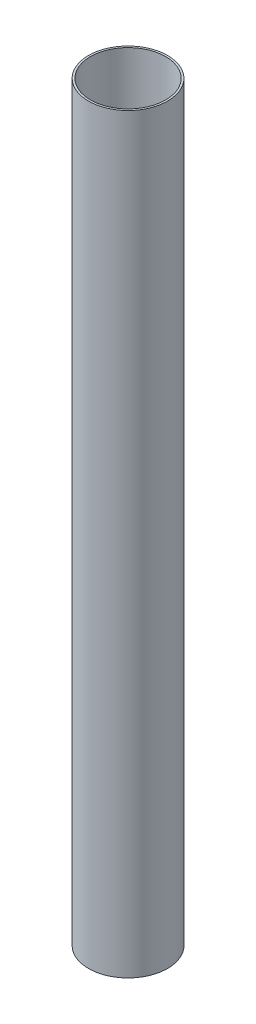
SolidWorks part; units mm, degrees
material "6063-T6"
ref_plane "Front Plane" through (0, 0, 0) normal (0, 0, 1) x (1, 0, 0)
ref_plane "Top Plane" through (0, 0, 0) normal (0, 1, 0) x (1, 0, 0)
ref_plane "Right Plane" through (0, 0, 0) normal (1, 0, 0) x (0, 0, -1)
sketch "Sketch1" plane through (0, 0, 0) normal (0, 1, 0) x (1, 0, 0)
  circle A0 centre (0, 0) radius 24.1554
  circle A1 centre (0, 0) radius 25.4
  dimension "D1" = 50.8
  dimension "D2" = 1.2446
extrude "body" add sketch "Sketch1" along normal blind 482.6
